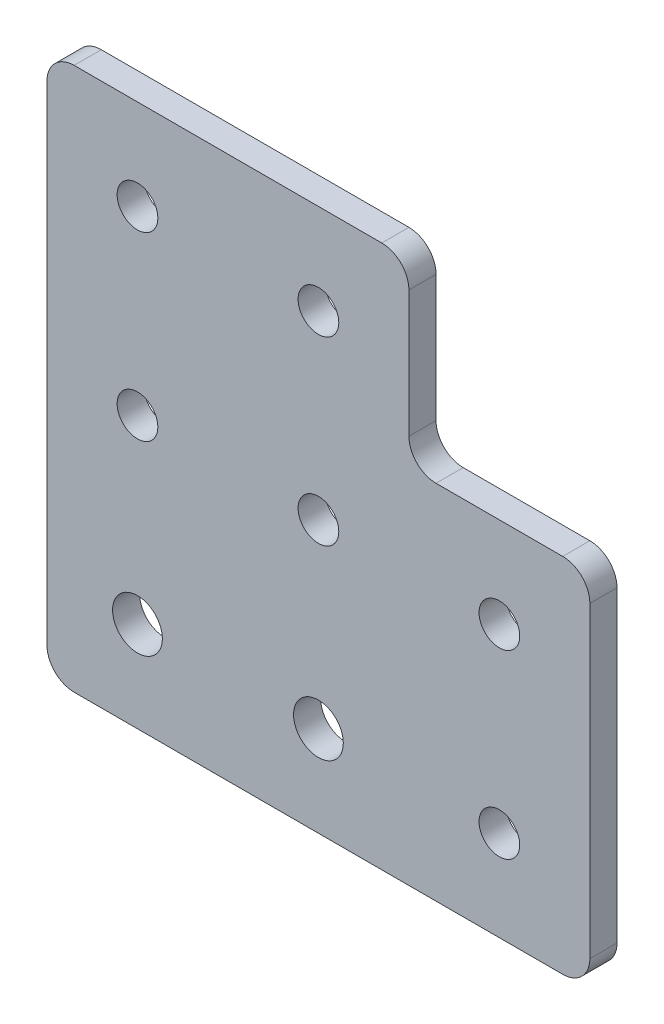
SolidWorks part; units mm, degrees
ref_plane "Płaszczyzna przednia" through (0, 0, 0) normal (0, 0, 1) x (1, 0, 0)
ref_plane "Płaszczyzna górna" through (0, 0, 0) normal (0, 1, 0) x (1, 0, 0)
ref_plane "Płaszczyzna prawa" through (0, 0, 0) normal (1, 0, 0) x (0, 0, -1)
sketch "Szkic1" plane through (0, 0, 0) normal (0, 0, 1) x (1, 0, 0)
  line L1 (-31.6286, 50.3888) -> (8.3714, 50.3888)
  line L2 (-31.6286, 50.3888) -> (-31.6286, -9.6112)
  line L3 (-31.6286, -9.6112) -> (-11.6286, -9.6112)
  line L4 (8.3714, 50.3888) -> (8.3714, 30.3888)
  line L5 (-31.6286, -9.6112) -> (28.3714, -9.6112)
  line L6 (-31.6286, -9.6112) -> (-31.6286, 10.3888)
  line L7 (8.3714, 30.3888) -> (28.3714, 30.3888)
  line L8 (28.3714, -9.6112) -> (28.3714, 30.3888)
  circle A0 centre (-21.6286, 40.3888) radius 2.25
  circle A1 centre (-1.6286, 40.3888) radius 2.25
  circle A2 centre (-21.6286, 20.3888) radius 2.25
  circle A3 centre (-21.6286, 0.3888) radius 2.75
  circle A4 centre (-1.6286, 20.3888) radius 2.25
  circle A5 centre (-1.6286, 0.3888) radius 2.75
  circle A6 centre (18.3714, 20.3888) radius 2.25
  circle A7 centre (18.3714, 0.3888) radius 2.25
  point P10 (0, 0)
  point P13 (-3.6382, 40.3888)
  point P16 (-21.6286, 20.0037)
  point P19 (-21.6286, -0.9269)
  point P22 (-3.6382, 19.2769)
  point P25 (-3.6382, -1.8717)
  point P28 (18.3098, 17.8234)
  point P31 (18.3098, -1.8717)
  dimension "D4" = 4.5
  dimension "D21" = 20
  dimension "D22" = 20
  dimension "D23" = 20
  dimension "D24" = 10
  dimension "D25" = 10
  dimension "D26" = 5.5
  dimension "D27" = 5.5
  dimension "D1" = 40
  dimension "D2" = 40
  dimension "D3" = 60
  dimension "D5" = 10
  dimension "D6" = 60
  dimension "D7" = 10
  dimension "D8" = 10
  dimension "D9" = 10
  dimension "D10" = 20
  dimension "D11" = 10
  dimension "D12" = 10
  dimension "D13" = 10
  dimension "D14" = 10
  dimension "D15" = 10
  dimension "D16" = 10
  dimension "D17" = 20
  dimension "D18" = 20
  dimension "D19" = 20
  dimension "D20" = 20
extrude "Dodanie-wyciągnięcie1" add sketch "Szkic1" along normal blind 3 contours L5 L8 L7 L4 L1 L2 L3 A7 A6 A5 A4 A3 A2 A1 A0
fillet "Zaokrąglenie1" radius 3 5 edges at (28.3714, -9.6112, 1.5) (28.3714, 30.3888, 1.5) (8.3714, 50.3888, 1.5) (-31.6286, -9.6112, 1.5) (-31.6286, 50.3888, 1.5)
fillet "Zaokrąglenie2" radius 3 1 edges at (8.3714, 30.3888, 1.5)
